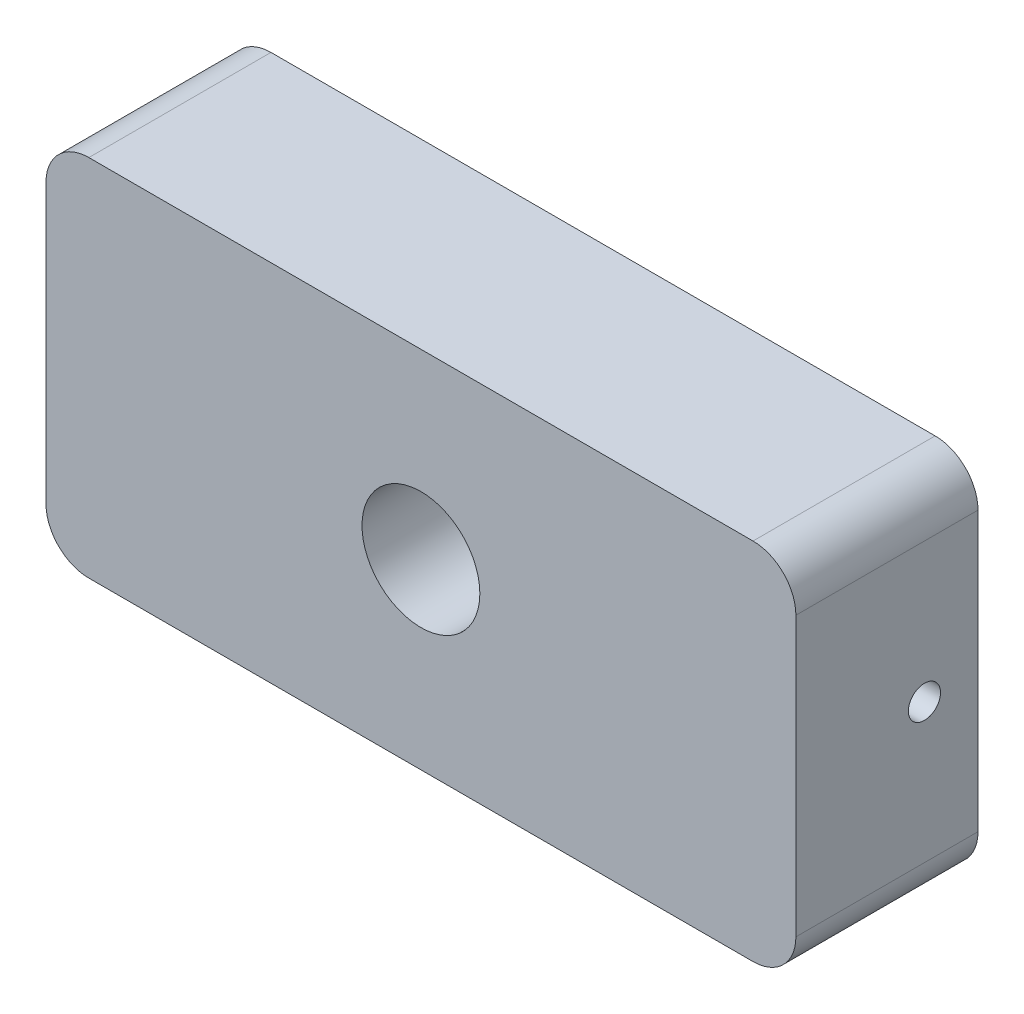
SolidWorks part; units mm, degrees
ref_plane "Alzado" through (0, 0, 0) normal (0, 0, 1) x (1, 0, 0)
ref_plane "Planta" through (0, 0, 0) normal (0, 1, 0) x (1, 0, 0)
ref_plane "Vista lateral" through (0, 0, 0) normal (1, 0, 0) x (0, 0, -1)
sketch "Croquis1" plane through (0, 0, 0) normal (0, 0, 1) x (1, 0, 0)
  line L0 (229.0197, 38.2053) -> (229.0197, 6.7614) construction
  line L1 (229.0197, 38.2053) -> (229.0197, 71.6385) construction
  line L2 (264.0197, 21.2053) -> (194.0197, 21.2053)
  line L4 (264.0197, 55.2053) -> (194.0197, 55.2053)
  line L5 (194.0197, 21.2053) -> (194.0197, 55.2053)
  line L6 (239.0942, 33.3119) -> (194.0197, 55.2053) construction
  line L7 (239.0942, 43.0986) -> (194.0197, 21.2053) construction
  line L8 (218.9452, 43.0986) -> (264.0197, 21.2053) construction
  line L9 (218.9452, 33.3119) -> (264.0197, 55.2053) construction
  line L10 (264.0197, 21.2053) -> (264.0197, 55.2053)
  circle A0 centre (229.0197, 38.2053) radius 11.2
  circle A1 centre (201.3197, 38.2053) radius 4.1
  circle A2 centre (256.7197, 38.2053) radius 4.1
  point P6 (229.0197, 21.2053)
  point P19 (229.0197, 55.2053)
  dimension "D1" = 22.4
  dimension "D2" = 8.2
extrude "Saliente-Extruir1" add sketch "Croquis1" along normal blind 9
sketch "Croquis2" plane through (0, 0, 9) normal (0, 0, 1) x (1, 0, 0)
  line L0 (264.0197, 21.2053) -> (264.0197, 55.2053) construction
  line L1 (194.0197, 21.2053) -> (264.0197, 21.2053)
  line L2 (194.0197, 21.2053) -> (194.0197, 55.2053)
  line L3 (194.0197, 55.2053) -> (264.0197, 55.2053)
  line L4 (264.0197, 21.2053) -> (264.0197, 55.2053)
  line L5 (194.0197, 21.2053) -> (264.0197, 55.2053) construction
  line L6 (194.0197, 55.2053) -> (264.0197, 21.2053) construction
  circle A0 centre (229.0197, 38.2053) radius 5.5
  point P0 (229.0197, 38.2053)
  dimension "D1" = 11
extrude "Saliente-Extruir2" add sketch "Croquis2" along normal blind 8
sketch "Sketch1" plane through (194.0197, 0, 0) normal (-1, 0, 0) x (0, 0, 1)
  line L2 (0, 55.2053) -> (0, 21.2053) construction
  line L3 (0, 37.982) -> (5, 37.982) construction
  circle A0 centre (5, 37.982) radius 1.5
  dimension "D1" = 3
  dimension "D2" = 5
extrude "Cut-Extrude1" cut sketch "Sketch1" against normal up to next
sketch "Sketch2" plane through (264.0197, 0, 0) normal (1, 0, 0) x (0, 0, -1)
  line L0 (698.05, 62.3467) -> (701.05, 62.3467) construction
  line L1 (0, 38.2053) -> (-5, 38.2053) construction
  line L2 (0, 21.2053) -> (0, 55.2053) construction
  circle A0 centre (701.05, 62.3467) radius 1.5
  circle A2 centre (-5, 38.2053) radius 1.5
  dimension "D2" = 3
  dimension "D1" = 5
extrude "Cut-Extrude2" cut sketch "Sketch2" against normal up to next contours A2
fillet "Fillet1" radius 4 4 edges at (264.0197, 21.2053, 8.5) (264.0197, 55.2053, 8.5) (194.0197, 55.2053, 8.5) (194.0197, 21.2053, 8.5)
